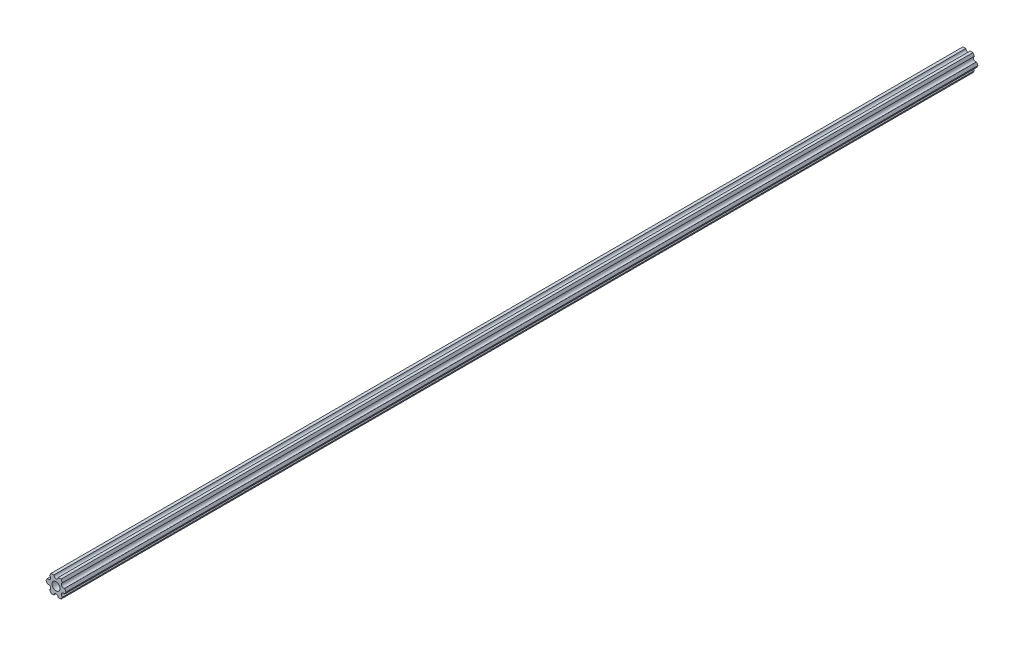
SolidWorks part; units mm, degrees
ref_plane "Front Plane" through (0, 0, 0) normal (0, 0, 1) x (1, 0, 0)
ref_plane "Top Plane" through (0, 0, 0) normal (0, 1, 0) x (1, 0, 0)
ref_plane "Right Plane" through (0, 0, 0) normal (1, 0, 0) x (0, 0, -1)
sketch "Sketch1" plane through (0, 0, 0) normal (0, 0, 1) x (1, 0, 0)
  line L0 (-1.5875, 6.35) -> (-3.6662, 6.35)
  line L1 (7.3323, 0) -> (6.293, 1.8002)
  line L2 (3.6662, 6.35) -> (1.5875, 6.35)
  line L3 (-3.6662, 6.35) -> (-4.7055, 4.5498)
  line L4 (-7.3323, 0) -> (-6.293, -1.8002)
  line L5 (-3.6662, -6.35) -> (-1.5875, -6.35)
  line L6 (3.6662, -6.35) -> (4.7055, -4.5498)
  line L7 (-6.293, 1.8002) -> (-7.3323, 0)
  line L8 (-4.7055, -4.5498) -> (-3.6662, -6.35)
  line L9 (1.5875, -6.35) -> (3.6662, -6.35)
  line L10 (6.293, -1.8002) -> (7.3323, 0)
  line L11 (4.7055, 4.5498) -> (3.6662, 6.35)
  circle A0 centre (0, 0) radius 2.9337
  arc A2 (-1.5875, 6.35) -> (1.5875, 6.35) centre (0, 6.35) ccw
  arc A3 (4.7055, 4.5498) -> (6.293, 1.8002) centre (5.4993, 3.175) ccw
  arc A4 (6.293, -1.8002) -> (4.7055, -4.5498) centre (5.4993, -3.175) ccw
  arc A5 (1.5875, -6.35) -> (-1.5875, -6.35) centre (0, -6.35) ccw
  arc A6 (-4.7055, -4.5498) -> (-6.293, -1.8002) centre (-5.4993, -3.175) ccw
  arc A7 (-6.293, 1.8002) -> (-4.7055, 4.5498) centre (-5.4993, 3.175) ccw
  dimension "D1" = 5.8674
  dimension "D3" = 3.175
  dimension "D4" = 6
extrude "Boss-Extrude1" add sketch "Sketch1" along normal blind 666.75
